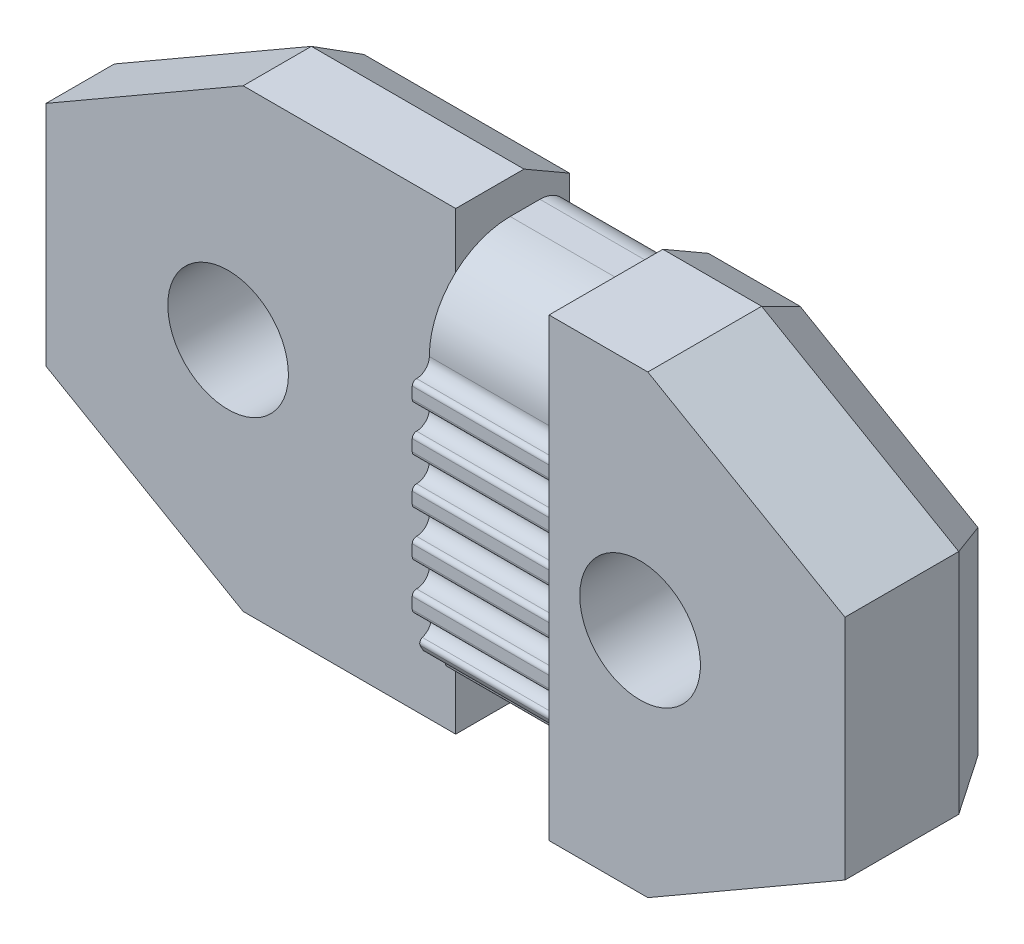
SolidWorks part; units mm, degrees
material "ABS"
ref_plane "Ebene vorne" through (0, 0, 0) normal (0, 0, 1) x (1, 0, 0)
ref_plane "Ebene oben" through (0, 0, 0) normal (0, 1, 0) x (1, 0, 0)
ref_plane "Ebene rechts" through (0, 0, 0) normal (1, 0, 0) x (0, 0, -1)
sketch "Skizze1" plane through (0, 0, 0) normal (0, 0, 1) x (1, 0, 0)
  line L0 (0, 0) -> (0, 15)
  line L1 (-10.615, 3.565) -> (-7.4598, 1.9054) construction
  line L2 (-8.7123, 0.5502) -> (-10.615, 3.565) construction
  line L3 (-7.3231, 2.8205) -> (-10.615, 3.565) construction
  line L4 (-8.1364, 1.2743) -> (-10.615, 3.565) construction
  line L5 (-9.7799, 0.8767) -> (-10.615, 3.565) construction
  line L6 (-7.05, 8.0688) -> (-7.05, 7.5688)
  line L7 (-7.05, 10.0688) -> (-7.05, 9.5688)
  line L8 (-7.05, 6.0688) -> (-7.05, 5.5688)
  line L9 (-7.05, 4.0688) -> (-7.05, 3.565)
  line L10 (-7.24, 4.2588) -> (-7.24, 3.565) construction
  line L11 (-7.8, 4.8188) -> (-7.8, 3.565) construction
  line L12 (-10.615, 3.565) -> (-7.05, 3.565) construction
  line L13 (-10.615, 3.565) -> (-10.615, 0) construction
  line L14 (-7.05, 12.0688) -> (-7.05, 11.5688)
  line L15 (-7.24, 12.2588) -> (-9.15, 12.2588)
  line L16 (-10.615, 4) -> (-9.15, 4)
  line L17 (0, 15) -> (-6, 15)
  line L18 (-6, 15) -> (-6, 0)
  line L19 (-6, 0) -> (0, 0)
  line L20 (-10.615, 4) -> (-10.615, 0) construction
  line L21 (-9.15, 4) -> (-9.15, 12.2588)
  line L22 (-10.615, 0) -> (-10.8638, 0)
  line L23 (-11.6138, 0.75) -> (-13.96, 0.75)
  line L24 (-13.96, 0.75) -> (-13.96, 4)
  line L25 (-13.96, 4) -> (-10.615, 4)
  line L27 (-7.05, 14.0688) -> (-7.05, 13.5688) [skipped]
  arc A0 (-8.5951, 0.6274) -> (-8.5493, 0.896) centre (-8.7028, 0.784) ccw
  arc A1 (-8.5493, 0.896) -> (-7.7918, 1.7157) centre (-8.1364, 1.2743) cw
  arc A2 (-7.7918, 1.7157) -> (-7.5276, 1.7825) centre (-7.6922, 1.8775) ccw
  arc A3 (-8.5951, 0.6274) -> (-8.8325, 0.4776) centre (-10.615, 3.565) cw
  arc A4 (-10.1606, 0.2207) -> (-10.3345, 0.0111) centre (-10.3495, 0.2005) cw
  arc A5 (-9.0947, 0.5518) -> (-10.1606, 0.2207) centre (-9.6138, 0.3419) ccw
  arc A6 (-8.8325, 0.4776) -> (-9.0947, 0.5518) centre (-8.9275, 0.6422) cw
  arc A7 (-10.3345, 0.0111) -> (-10.615, 0) centre (-10.615, 3.565) cw
  arc A8 (-7.24, 7.3788) -> (-7.24, 6.2588) centre (-7.24, 6.8188) ccw
  arc A9 (-7.24, 7.3788) -> (-7.05, 7.5688) centre (-7.24, 7.5688) ccw
  arc A10 (-7.05, 8.0688) -> (-7.24, 8.2588) centre (-7.24, 8.0688) ccw
  arc A11 (-7.24, 9.3788) -> (-7.24, 8.2588) centre (-7.24, 8.8188) ccw
  arc A12 (-7.24, 9.3788) -> (-7.05, 9.5688) centre (-7.24, 9.5688) ccw
  arc A13 (-7.05, 6.0688) -> (-7.24, 6.2588) centre (-7.24, 6.0688) ccw
  arc A14 (-7.24, 5.3788) -> (-7.05, 5.5688) centre (-7.24, 5.5688) ccw
  arc A15 (-7.24, 5.3788) -> (-7.24, 4.2588) centre (-7.24, 4.8188) ccw
  arc A16 (-7.05, 4.0688) -> (-7.24, 4.2588) centre (-7.24, 4.0688) ccw
  arc A17 (-7.24, 3.565) -> (-10.615, 0.19) centre (-10.615, 3.565) cw construction
  arc A18 (-7.8, 3.565) -> (-10.615, 0.75) centre (-10.615, 3.565) cw construction
  arc A19 (-7.05, 3.565) -> (-7.2453, 3.3751) centre (-7.24, 3.565) cw
  arc A20 (-7.2453, 3.3751) -> (-7.4916, 2.2864) centre (-7.3231, 2.8205) ccw
  arc A21 (-7.4916, 2.2864) -> (-7.3969, 2.0309) centre (-7.5685, 2.1127) cw
  arc A22 (-7.3969, 2.0309) -> (-7.5276, 1.7825) centre (-10.615, 3.565) cw
  arc A23 (-7.05, 10.0688) -> (-7.24, 10.2588) centre (-7.24, 10.0688) ccw
  arc A24 (-7.24, 11.3788) -> (-7.24, 10.2588) centre (-7.24, 10.8188) ccw
  arc A25 (-7.24, 11.3788) -> (-7.05, 11.5688) centre (-7.24, 11.5688) ccw
  arc A26 (-7.05, 12.0688) -> (-7.24, 12.2588) centre (-7.24, 12.0688) ccw
  arc A27 (-10.8638, 0) -> (-11.0538, 0.19) centre (-10.8638, 0.19) cw
  arc A28 (-11.0538, 0.19) -> (-11.6138, 0.75) centre (-11.6138, 0.19) ccw
  arc A33 (-7.05, 3.565) -> (-10.615, 0) centre (-10.615, 3.565) cw construction
  arc A50 (-7.24, 13.3788) -> (-7.24, 12.2588) centre (-7.24, 12.8188) ccw [skipped]
  arc A51 (-7.24, 13.3788) -> (-7.05, 13.5688) centre (-7.24, 13.5688) ccw [skipped]
  arc A52 (-7.05, 14.0688) -> (-7.24, 14.2588) centre (-7.24, 14.0688) ccw [skipped]
  point P59 (-7.8693, 2.944)
  dimension "D3" = 2
  dimension "D9" = 3.565
  dimension "D11" = 0.56
  dimension "D13" = 3.375
  dimension "D2" = 15
  dimension "D5" = 30
  dimension "D6" = 1.8
  dimension "D7" = 6
  dimension "D8" = 30
  dimension "D10" = 2
  dimension "D4" = 0.75
  dimension "D12" = 5
  dimension "D14" = 4
  dimension "D15" = 2.1
  dimension "D16" = 2
  dimension "D17" = 4.81
extrude "Aufsatz-Linear austragen1" add sketch "Skizze1" along normal blind 6.1
sketch "Skizze2" plane through (0, 0, 6.1) normal (0, 0, 1) x (1, 0, 0)
  line L1 (-6, 15) -> (0, 15)
  line L2 (-6, 15) -> (-6, 0)
  line L3 (-6, 0) -> (0, 0)
  line L4 (0, 15) -> (0, 0)
extrude "Schnitt-Linear austragen1" cut sketch "Skizze2" against normal up to surface (6.1 mm away) up to face at (-3, 7.5, 0)
sketch "Skizze3" plane through (-9.15, 0, 0) normal (-1, 0, 0) x (0, 0, 1)
  line L0 (6.1, 16.37) -> (0, 16.37)
  line L1 (0, -2.13) -> (-13, -2.13)
  line L2 (0, -2.13) -> (0, 17.87)
  line L3 (0, 17.87) -> (-13, 17.87)
  line L4 (-13, -2.13) -> (-13, 17.87)
  line L6 (-4, 7.87) -> (0, 7.87) construction
  line L9 (0, 17.87) -> (0, 12.2588)
  line L10 (0, 12.2588) -> (6.1, 12.2588)
  line L11 (6.1, 16.37) -> (6.1, 12.2588)
  line L18 (0, 4) -> (0, 12.2588) construction
  line L19 (6.1, 0) -> (0, 0) construction
  line L20 (6.1, 4) -> (6.1, 12.2588) construction
  line L21 (6.1, 12.2588) -> (0, 12.2588) construction
  circle A0 centre (-4, 7.87) radius 2.65
  dimension "D4" = 5.3
  dimension "D1" = 20
  dimension "D2" = 2.13
  dimension "D3" = 4
  dimension "D5" = 13
  dimension "D6" = 1.5
extrude "Aufsatz-Linear austragen2" add sketch "Skizze3" against normal blind 2.19
sketch "Skizze15" plane through (0, 0, 6.1) normal (0, 0, 1) x (1, 0, 0)
  line L0 (-7.8, 12.8188) -> (-7.8, 15.07)
  line L1 (-6.96, 12.2588) -> (-7.24, 12.2588) construction
  line L2 (-6.96, 12.2588) -> (-6.96, 16.37)
  line L3 (-6.96, 16.37) -> (-6.96, 12.2588) construction
  line L4 (-6.96, 16.37) -> (-9.1, 16.37)
  line L5 (-6.96, 16.37) -> (-9.15, 16.37) construction
  line L6 (-7.24, 12.2588) -> (-6.96, 12.2588)
  arc A0 (-7.8, 15.07) -> (-9.1, 16.37) centre (-9.1, 15.07) ccw
  arc A1 (-7.24, 12.2588) -> (-7.8, 12.8188) centre (-7.24, 12.8188) cw
  arc A5 (-7.24, 11.3788) -> (-7.24, 10.2588) centre (-7.24, 10.8188) ccw construction
  dimension "D1" = 1.3
extrude "Schnitt-Linear austragen7" cut sketch "Skizze15" against normal up to surface (6.1 mm away) up to face at (-7.5941, 5.4921, 0)
sketch "Skizze4" plane through (-9.15, 0, 0) normal (-1, 0, 0) x (0, 0, 1)
  line L1 (6.1, 16.37) -> (6.1, 17.87)
  line L2 (6.1, 16.37) -> (6.1, -2.13)
  line L3 (6.1, -2.13) -> (24.1, -2.13)
  line L4 (24.1, 17.87) -> (24.1, -2.13)
  line L5 (0, -2.13) -> (-13, -2.13) construction
  line L7 (6.1, 4) -> (6.1, 16.37) construction
  line L8 (-4, 7.87) -> (16.1, 7.87) construction
  line L9 (6.1, 17.87) -> (24.1, 17.87)
  line L18 (6.1, 16.37) -> (0, 16.37)
  line L19 (6.1, 16.37) -> (0, 16.37)
  line L20 (0, 16.37) -> (0, 17.87)
  line L21 (0, 16.37) -> (0, 17.87)
  line L22 (0, 17.87) -> (-13, 17.87)
  line L23 (6.1, 4) -> (6.1, 16.37)
  line L24 (0, 17.87) -> (-13, 17.87)
  line L25 (-13, 17.87) -> (-13, -2.13)
  line L26 (-13, -2.13) -> (0, -2.13)
  line L27 (0, -2.13) -> (0, 0.6557)
  line L28 (0, 0.6557) -> (0, 4)
  line L29 (0, 4) -> (6.1, 4)
  line L34 (6.1, 4) -> (6.1, 16.37)
  line L36 (-13, 17.87) -> (-13, -2.13)
  line L37 (-13, -2.13) -> (0, -2.13)
  line L38 (0, -2.13) -> (0, 0.6557)
  line L39 (0, 0.6557) -> (0, 4)
  line L40 (0, 4) -> (6.1, 4)
  circle A0 centre (-4, 7.87) radius 2.65 construction
  circle A1 centre (-4, 7.87) radius 2.65 construction
  circle A2 centre (16.1, 7.87) radius 2.65
  dimension "D2" = 10
  dimension "D3" = 8
  dimension "D1" = 0
extrude "Aufsatz-Linear austragen3" add sketch "Skizze4" along normal up to surface (4.81 mm away)
sketch "Skizze5" plane through (-9.15, 0, 0) normal (1, 0, 0) x (0, 0, -1)
  line L6 (-6.1, 17.87) -> (-24.1, 17.87)
  line L7 (-6.1, 0.6557) -> (-6.1, 16.37)
  line L8 (-6.1, 17.87) -> (-24.1, 17.87)
  line L9 (-24.1, 17.87) -> (-24.1, -2.13)
  line L10 (-24.1, -2.13) -> (-6.1, -2.13)
  line L11 (-6.1, 16.37) -> (-6.1, 17.87)
  line L12 (-6.1, -2.13) -> (-6.1, 0.6557)
  line L13 (-6.1, 16.37) -> (-6.1, 17.87)
  line L14 (-6.1, 0.6557) -> (-6.1, 16.37)
  line L15 (-6.1, -2.13) -> (-6.1, 0.6557)
  line L16 (-24.1, 17.87) -> (-24.1, -2.13)
  line L17 (-24.1, -2.13) -> (-6.1, -2.13)
  circle A0 centre (-16.1, 7.87) radius 2.65 construction
  circle A1 centre (-16.1, 7.87) radius 2.65
  dimension "D1" = 0
extrude "Aufsatz-Linear austragen4" add sketch "Skizze5" along normal offset from surface (0.19 mm away) 1.91 up to face at (-7.05, 3.8169, 3.05)
chamfer "Fase1" distance 5 angle 60 4 edges at (-11.46, -2.13, 24.1) (-10.46, -2.13, -13) (-11.46, 17.87, 24.1) (-10.46, 17.87, -13)
chamfer "Fase2" distance 2 angle 30 10 edges at (-13.96, -2.13, 10.7699) (-13.96, 0.37, 19.7699) (-13.96, 7.87, 24.1) (-13.96, 0.37, -8.6699) (-13.96, -2.13, -2.1699) (-13.96, 7.87, -13) (-13.96, 17.87, 10.7699) (-13.96, 15.37, 19.7699) (-13.96, 17.87, -2.1699) (-13.96, 15.37, -8.6699)
sketch "Skizze11" plane through (0, -2.13, 0) normal (0, -1, 0) x (1, 0, 0)
  line L0 (-13.96, 7.6) -> (-13.96, 6.1)
  line L2 (-13.96, 0) -> (-13.96, -1.5)
  line L3 (-12.46, 1.5) -> (-12.46, 4.6)
  line L4 (-10.96, 1.5) -> (-10.96, 4.6)
  arc A0 (-13.96, 6.1) -> (-12.46, 4.6) centre (-13.96, 4.6) cw
  arc A1 (-13.96, 0) -> (-12.46, 1.5) centre (-13.96, 1.5) ccw
  arc A2 (-13.96, -1.5) -> (-10.96, 1.5) centre (-13.96, 1.5) ccw
  arc A3 (-13.96, 7.6) -> (-10.96, 4.6) centre (-13.96, 4.6) cw
  dimension "D1" = 1.5
  dimension "D2" = 1.5
extrude "Schnitt-Linear austragen8" cut sketch "Skizze11" against normal blind 2 from offset 14
sketch "Skizze13" plane through (0, 0, 24.1) normal (0, 0, 1) x (1, 0, 0)
  line L0 (-13.96, 3.5367) -> (-13.96, 12.2033) construction
  line L1 (-13.96, 3.5367) -> (-13.96, 12.2033) construction
  line L2 (-13.96, 7.87) -> (-11.46, 7.87) construction
  line L3 (-12.96, 5.87) -> (-12.96, 9.87)
  line L4 (-11.46, 5.87) -> (-11.46, 9.87)
  line L5 (-13.96, 4.87) -> (-13.96, 3.37)
  line L6 (-13.96, 10.87) -> (-13.96, 12.37)
  arc A0 (-13.96, 3.37) -> (-11.46, 5.87) centre (-13.96, 5.87) ccw
  arc A1 (-13.96, 4.87) -> (-12.96, 5.87) centre (-13.96, 5.87) ccw
  arc A2 (-13.96, 10.87) -> (-12.96, 9.87) centre (-13.96, 9.87) cw
  arc A3 (-13.96, 12.37) -> (-11.46, 9.87) centre (-13.96, 9.87) cw
  point P15 (-12.96, 7.87)
  dimension "D1" = 1.5
  dimension "D2" = 1
  dimension "D3" = 6
extrude "Schnitt-Linear austragen5" cut sketch "Skizze13" against normal blind 2.5 from offset 13.5
fillet "Verrundung1" radius 1.3 1 edges at (-13.96, 16.37, 3.05)
sketch "Skizze16" plane through (0, 0, 6.1) normal (0, 0, 1) x (1, 0, 0)
  line L0 (-7.8, 4.8188) -> (-7.8, 12.8188) construction
  line L1 (-7.8, 15.07) -> (-7.8, 12.8188) construction
  line L2 (-9.1, 16.37) -> (-12.66, 16.37) construction
  line L3 (-7.8, 15.07) -> (-7.8, 12.8188)
  line L4 (-9.1, 16.37) -> (-12.66, 16.37)
  arc A0 (-7.24, 5.3788) -> (-7.24, 4.2588) centre (-7.24, 4.8188) ccw construction
  arc A1 (-7.8, 15.07) -> (-9.1, 16.37) centre (-9.1, 15.07) ccw construction
  arc A2 (-12.66, 16.37) -> (-13.96, 15.07) centre (-12.66, 15.07) ccw construction
  arc A3 (-7.8, 15.07) -> (-9.1, 16.37) centre (-9.1, 15.07) ccw
  arc A4 (-12.66, 16.37) -> (-13.96, 15.07) centre (-12.66, 15.07) ccw construction
  arc A5 (-7.8, 12.8188) -> (-11.3512, 16.37) centre (-11.3512, 12.8188) ccw
  line M1 (-8.96, 16.3624) -> (-8.96, 0.455)
  line M30 (-7.8, 12.8188) -> (-7.8, 15.07)
  arc M31 (-7.8, 15.07) -> (-8.96, 16.3624) centre (-9.1, 15.07) ccw
extrude "Schnitt-Linear austragen9" cut sketch "Skizze16" against normal up to surface (6.1 mm away) contours A5 M30 M31 M1 | A5 A3 L4 M1
move or copy body "Körper-Verschieben/Kopieren1" bodies to move or copy 120 copy no rotation origin (-10.55, 0, 5.55) rotation axis (0, -1, 0) rotation angle 90
